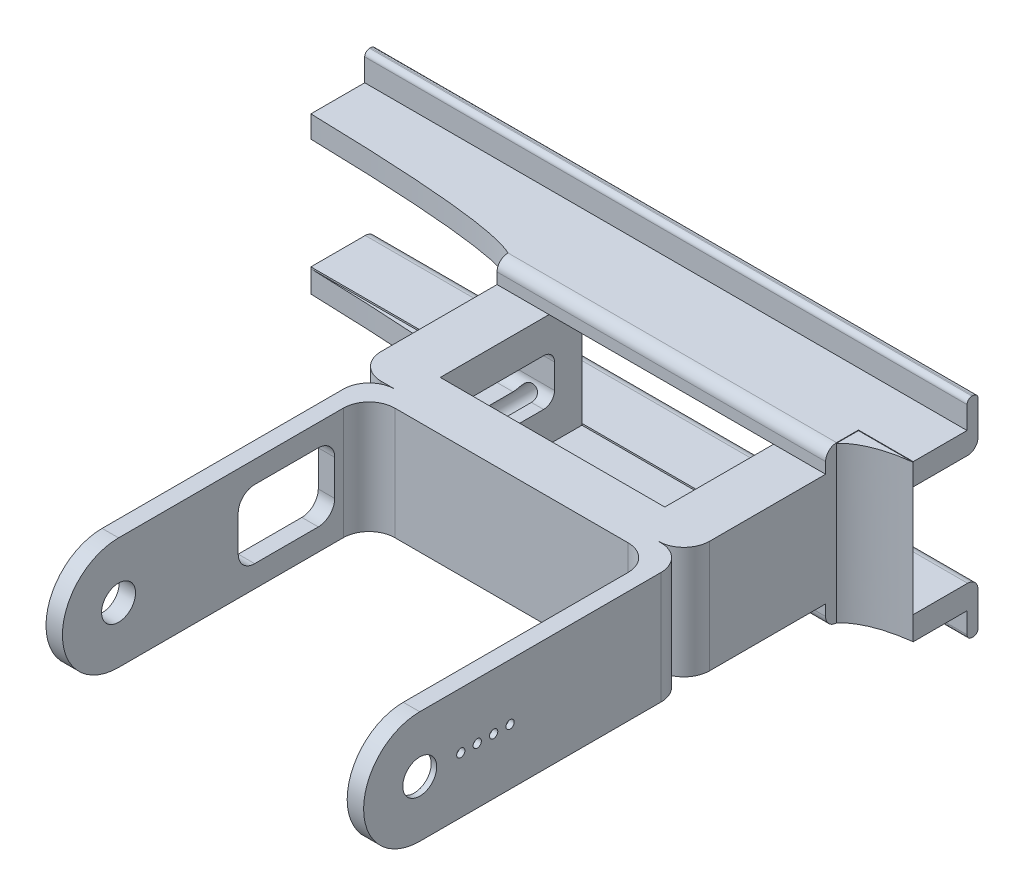
SolidWorks part; units mm, degrees
ref_plane "Vorne" through (0, 0, 0) normal (0, 0, 1) x (1, 0, 0)
ref_plane "Oben" through (0, 0, 0) normal (0, 1, 0) x (1, 0, 0)
ref_plane "Rechts" through (0, 0, 0) normal (1, 0, 0) x (0, 0, -1)
sketch "Skizze1" plane through (0, 0, 0) normal (0, 1, 0) x (1, 0, 0)
  line L1 (0, 0) -> (58, 0)
  line L2 (0, 0) -> (0, 54.3)
  line L3 (4.7, 59) -> (53.3, 59)
  line L4 (58, 0) -> (58, 54.3)
  line L5 (55, 0) -> (3, 0)
  line L6 (55, 0) -> (55, 51.3)
  line L7 (50.3, 56) -> (7.7, 56)
  line L8 (3, 0) -> (3, 51.3)
  arc A0 (55, 51.3) -> (50.3, 56) centre (50.3, 51.3) ccw
  arc A1 (7.7, 56) -> (3, 51.3) centre (7.7, 51.3) ccw
  arc A2 (53.3, 59) -> (58, 54.3) centre (53.3, 54.3) cw
  arc A3 (0, 54.3) -> (4.7, 59) centre (4.7, 54.3) cw
  point P17 (0, 59)
  dimension "D6" = 4.7
  dimension "D7" = 4.7
  dimension "D8" = 4.7
  dimension "D1" = 59
  dimension "D2" = 58
  dimension "D3" = 3
  dimension "D4" = 3
  dimension "D5" = 3
extrude "Aufsatz-Linear austragen1" add sketch "Skizze1" along normal blind 20.5 contours L1 L8 L7 L6 L4 L3 L2
sketch "Skizze2" plane through (58, 0, 0) normal (1, 0, 0) x (0, 0, -1)
  line L1 (10.25, 20.5) -> (0, 20.5)
  line L2 (0, 20.5) -> (0, 0)
  line L3 (0, 0) -> (10.25, 0)
  arc A0 (10.25, 20.5) -> (10.25, 0) centre (10.25, 10.25) ccw
  line M1 (0, 0) -> (54.3, 0)
  line M3 (54.3, 20.5) -> (0, 20.5)
  line M4 (0, 20.5) -> (0, 0)
  dimension "D1" = 10.25
  dimension "D2" = 10.25
extrude "Schnitt-Linear austragen1" cut sketch "Skizze2" against normal blind 85.1 contours A0 M3 M4 | A0 L2 M1
sketch "Skizze3" plane through (58, 0, 0) normal (1, 0, 0) x (0, 0, -1)
  circle A0 centre (10.25, 10.25) radius 3.1
  dimension "D1" = 6.2
extrude "Schnitt-Linear austragen2" cut sketch "Skizze3" against normal blind 87.42
sketch "Skizze4" plane through (55, 0, 0) normal (-1, 0, 0) x (0, 0, 1)
  line L2 (-12.8953, 4.3674) -> (-27.5, 7.5)
  line L3 (-13.2151, 15.9781) -> (-27.5, 12.5)
  arc A0 (-12.8953, 4.3674) -> (-13.2151, 15.9781) centre (-10.25, 10.25) ccw
  arc A1 (-27.5, 12.5) -> (-27.5, 7.5) centre (-27.5, 10) ccw
  arc A2 (-10.25, 0) -> (-10.25, 20.5) centre (-10.25, 10.25) ccw construction
  dimension "D1" = 0
extrude "Schnitt-Linear austragen3" cut sketch "Skizze4" against normal blind 2
sketch "Skizze5" plane through (57, 0, 0) normal (-1, 0, 0) x (0, 0, 1)
  circle A0 centre (-26.75, 10.2499) radius 0.75
  circle A1 centre (-23.75, 10.25) radius 0.75
  circle A2 centre (-20.75, 10.25) radius 0.75
  circle A3 centre (-17.75, 10.25) radius 0.75
  circle A4 centre (-10.25, 10.25) radius 3.1 construction
  dimension "D1" = 3
  dimension "D2" = 3
  dimension "D3" = 3
  dimension "D4" = 7.5
  dimension "D6" = 0
  dimension "D7" = 0
  dimension "D5" = 0
extrude "Schnitt-Linear austragen4" cut sketch "Skizze5" against normal blind 2
sketch "Skizze6" plane through (0, 0, 0) normal (0, -1, 0) x (1, 0, 0)
  line L0 (4.7, -59) -> (53.3, -59) construction
  line L5 (29, -59) -> (2.2, -59)
  line L7 (27.5, -65) -> (-2.5, -65)
  line L8 (-2.5, -63.7) -> (-2.5, -65)
  line L10 (29, -59) -> (52.8, -59)
  line L12 (27.5, -65) -> (57.5, -65)
  line L13 (57.5, -63.7) -> (57.5, -65)
  arc A0 (52.8, -59) -> (57.5, -63.7) centre (52.8, -63.7) cw
  arc A1 (2.2, -59) -> (-2.5, -63.7) centre (2.2, -63.7) ccw
  point P11 (57.5, -59)
  dimension "D4" = 4.7
  dimension "D1" = 30
  dimension "D2" = 30
  dimension "D3" = 6
extrude "Aufsatz-Linear austragen2" add sketch "Skizze6" against normal through all
sketch "Skizze7" plane through (0, 0, -65) normal (0, 0, -1) x (-1, 0, 0)
  line L0 (2.5, 0) -> (-57.5, 0) construction
  line L1 (-57.5, 20.5) -> (-48, 20.5)
  line L2 (-57.5, 20.5) -> (-57.5, 0)
  line L3 (-57.5, 0) -> (-48, 0)
  line L4 (-48, 20.5) -> (-48, 0)
  line L7 (2.5, 20.5) -> (-7, 20.5)
  line L8 (2.5, 20.5) -> (2.5, 0)
  line L9 (2.5, 0) -> (-7, 0)
  line L10 (-7, 20.5) -> (-7, 0)
  dimension "D1" = 9.5
  dimension "D2" = 9.5
extrude "Aufsatz-Linear austragen3" add sketch "Skizze7" along normal blind 25.87
sketch "Skizze8" plane through (-2.5, 0, 0) normal (-1, 0, 0) x (0, 0, 1)
  line L0 (-63.7, 20.5) -> (-90.87, 20.5) construction
  line L1 (-83.87, 14.5) -> (-67.2, 14.5)
  line L2 (-85.87, 12.5) -> (-85.87, 8)
  line L3 (-83.87, 6) -> (-67.2, 6)
  line L4 (-65.2, 12.5) -> (-65.2, 8)
  line L5 (-63.7, 0) -> (-90.87, 0) construction
  line L7 (-90.87, 0) -> (-90.87, 20.5) construction
  line L8 (-63.7, 20.5) -> (-63.7, 0) construction
  arc A0 (-67.2, 14.5) -> (-65.2, 12.5) centre (-67.2, 12.5) cw
  arc A1 (-67.2, 6) -> (-65.2, 8) centre (-67.2, 8) ccw
  arc A2 (-85.87, 8) -> (-83.87, 6) centre (-83.87, 8) ccw
  arc A3 (-83.87, 14.5) -> (-85.87, 12.5) centre (-83.87, 12.5) ccw
  dimension "D5" = 2
  dimension "D1" = 6
  dimension "D2" = 6
  dimension "D3" = 5
  dimension "D4" = 1.5
extrude "Schnitt-Linear austragen5" cut sketch "Skizze8" against normal blind 18.09
sketch "Skizze9" plane through (0, 0, -90.87) normal (0, 0, -1) x (-1, 0, 0)
  circle A4 centre (-3.1, 5.5) radius 1.75
  circle A5 centre (-3.1, 15.5) radius 1.75
  circle A6 centre (-51.9, 5.5) radius 1.75
  circle A7 centre (-51.9, 15.5) radius 1.75
  dimension "D1" = 3.5
  dimension "D2" = 3.5
  dimension "D3" = 3.5
  dimension "D4" = 3.5
extrude "Schnitt-Linear austragen6" cut sketch "Skizze9" against normal blind 24.9
sketch "Skizze10" plane through (57.5, 0, 0) normal (1, 0, 0) x (0, 0, -1)
  line L1 (90.87, 20.5) -> (84.87, 20.5)
  line L2 (90.87, 20.5) -> (90.87, 24.5)
  line L3 (90.87, 24.5) -> (86.87, 24.5)
  line L4 (84.87, 20.5) -> (84.87, 22.5)
  line L5 (90.87, 0) -> (84.87, 0)
  line L6 (90.87, 0) -> (90.87, -4)
  line L7 (90.87, -4) -> (86.87, -4)
  line L8 (84.87, 0) -> (84.87, -2)
  arc A0 (86.87, -4) -> (84.87, -2) centre (86.87, -2) cw
  arc A1 (86.87, 24.5) -> (84.87, 22.5) centre (86.87, 22.5) ccw
  point P12 (84.87, -4)
  point P15 (84.87, 24.5)
  dimension "D5" = 2
  dimension "D1" = 4
  dimension "D2" = 6
  dimension "D3" = 4
  dimension "D4" = 6
extrude "Aufsatz-Linear austragen4" add sketch "Skizze10" against normal through all
sketch "Skizze11" plane through (-2.5, 0, 0) normal (-1, 0, 0) x (0, 0, 1)
  line L1 (-90.87, 24.5) -> (-100.7, 24.5)
  line L2 (-90.87, 24.5) -> (-90.87, 20.5)
  line L3 (-90.87, 20.5) -> (-100.7, 20.5)
  line L5 (-90.87, -4) -> (-100.7, -4)
  line L6 (-90.87, -4) -> (-90.87, 0.3)
  line L7 (-90.87, 0.3) -> (-100.7, 0.3)
  line L9 (-100.7, 0.3) -> (-100.8, 0.3)
  line L10 (-100.7, -4) -> (-100.7, -7.8)
  line L11 (-101.6, -8.7) -> (-101.8, -8.7)
  line L12 (-102.7, -1.6) -> (-102.7, -7.8)
  line L13 (-100.7, 20.5) -> (-100.8, 20.5)
  line L14 (-100.7, 24.5) -> (-100.7, 28.6)
  line L15 (-101.6, 29.5) -> (-101.8, 29.5)
  line L16 (-102.7, 22.4) -> (-102.7, 28.6)
  arc A0 (-100.7, -7.8) -> (-101.6, -8.7) centre (-101.6, -7.8) cw
  arc A1 (-101.8, -8.7) -> (-102.7, -7.8) centre (-101.8, -7.8) cw
  arc A2 (-100.7, 28.6) -> (-101.6, 29.5) centre (-101.6, 28.6) ccw
  arc A3 (-101.8, 29.5) -> (-102.7, 28.6) centre (-101.8, 28.6) ccw
  arc A4 (-100.8, 0.3) -> (-102.7, -1.6) centre (-100.8, -1.6) ccw
  arc A5 (-100.8, 20.5) -> (-102.7, 22.4) centre (-100.8, 22.4) cw
  point P20 (-100.7, -8.7)
  point P23 (-102.7, -8.7)
  point P26 (-100.7, 29.5)
  point P29 (-102.7, 29.5)
  point P32 (-102.7, 0.3)
  point P35 (-102.7, 20.5)
  dimension "D5" = 0.9
  dimension "D6" = 1.9
  dimension "D1" = 2
  dimension "D2" = 2
  dimension "D3" = 9
  dimension "D4" = 9
extrude "Aufsatz-Linear austragen5" add sketch "Skizze11" against normal blind 70 and the other way blind 40
sketch "Skizze12" plane through (0, 24.5, 0) normal (0, 1, 0) x (1, 0, 0)
  line L0 (-42.5, 90.87) -> (-2.5, 90.87)
  line L1 (-2.5, 90.87) -> (-2.5, 86.87)
  spline S0 degree 2 poles (-42.5, 90.87) (-9.0806, 90.0928) (-2.5, 86.87) knots 0 0 0 1 1 1
extrude "Aufsatz-Linear austragen6" add sketch "Skizze12" against normal blind 4
sketch "Skizze13" plane through (0, -4, 0) normal (0, -1, 0) x (1, 0, 0)
  line L0 (-2.5, -86.87) -> (-2.5, -90.87)
  line L1 (-2.5, -90.87) -> (-42.5, -90.87)
  spline S0 degree 2 poles (-42.5, -90.87) (-8.3202, -89.8307) (-2.5, -86.87) knots 0 0 0 1 1 1
extrude "Aufsatz-Linear austragen7" add sketch "Skizze13" against normal blind 4
sketch "Skizze14" plane through (0, -4, 0) normal (0, -1, 0) x (1, 0, 0)
  line L0 (57.5, -86.87) -> (57.5, -90.87)
  line L1 (57.5, -90.87) -> (67.5, -90.87)
  spline S0 degree 2 poles (57.5, -86.87) (60.4254, -89.995) (67.5, -90.87) knots 0 0 0 1 1 1
extrude "Aufsatz-Linear austragen8" add sketch "Skizze14" against normal blind 28.4
sketch "Skizze16" plane through (0, 0, 0) normal (-1, 0, 0) x (0, 0, 1)
  line L0 (-10.25, 0) -> (-54.3, 0) construction
  line L1 (-46.7212, 4) -> (-35.1003, 4)
  line L2 (-49.7212, 7) -> (-49.7212, 13.5)
  line L3 (-46.7212, 16.5) -> (-35.1003, 16.5)
  line L4 (-32.1003, 7) -> (-32.1003, 13.5)
  line L5 (-10.25, 20.5) -> (-54.3, 20.5) construction
  line L6 (-54.3, 20.5) -> (-54.3, 0) construction
  arc A0 (-46.7212, 4) -> (-49.7212, 7) centre (-46.7212, 7) cw
  arc A1 (-35.1003, 4) -> (-32.1003, 7) centre (-35.1003, 7) ccw
  arc A2 (-35.1003, 16.5) -> (-32.1003, 13.5) centre (-35.1003, 13.5) cw
  arc A3 (-49.7212, 13.5) -> (-46.7212, 16.5) centre (-46.7212, 13.5) cw
  dimension "D4" = 3
  dimension "D1" = 4
  dimension "D2" = 4
  dimension "D3" = 22.1997
extrude "Schnitt-Linear austragen7" cut sketch "Skizze16" against normal up to surface (3 mm away) up to face at (3, 10.25, -7.15)
